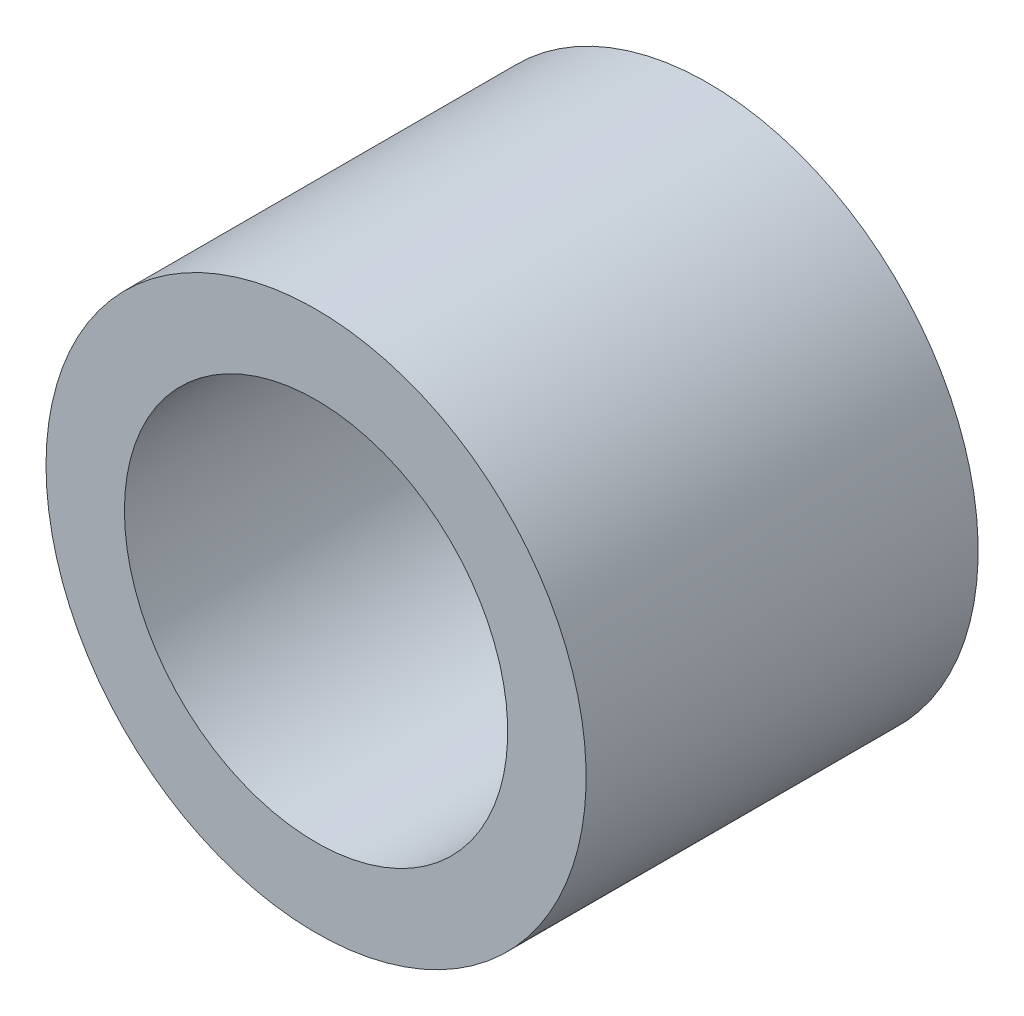
SolidWorks part; units mm, degrees
ref_plane "Alzado" through (0, 0, 0) normal (0, 0, 1) x (1, 0, 0)
ref_plane "Planta" through (0, 0, 0) normal (0, 1, 0) x (1, 0, 0)
ref_plane "Vista lateral" through (0, 0, 0) normal (1, 0, 0) x (0, 0, -1)
sketch "Croquis1" plane through (0, 0, 0) normal (0, 0, 1) x (1, 0, 0)
  circle A0 centre (0, 0) radius 15.5
  circle A1 centre (0, 0) radius 11
  dimension "D1" = 31
  dimension "D2" = 22
extrude "Saliente-Extruir1" add sketch "Croquis1" along normal blind 22.5
